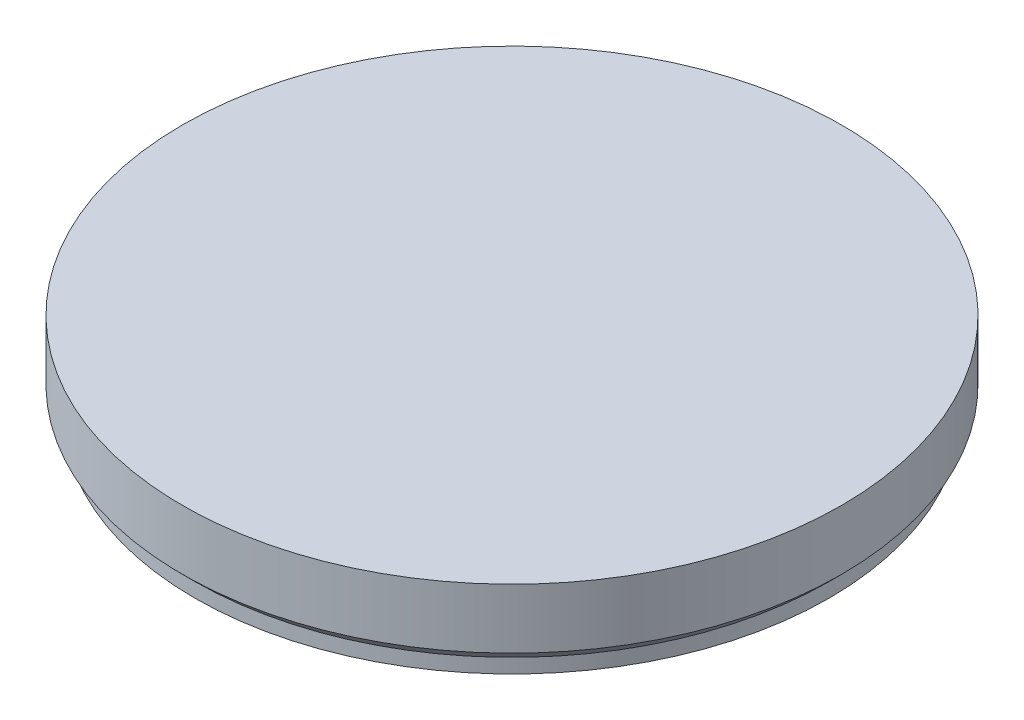
SolidWorks part; units mm, degrees
ref_plane "Front Plane" through (0, 0, 0) normal (0, 0, 1) x (1, 0, 0)
ref_plane "Top Plane" through (0, 0, 0) normal (0, 1, 0) x (1, 0, 0)
ref_plane "Right Plane" through (0, 0, 0) normal (1, 0, 0) x (0, 0, -1)
sketch "Sketch1" plane through (0, 0, 0) normal (0, 0, 1) x (1, 0, 0)
  line L0 (0, 12) -> (0, 15)
  line L1 (0, 15) -> (85, 15)
  line L2 (85, 15) -> (85, 10.5)
  line L3 (85, 10.5) -> (84, 10.5)
  line L4 (77, 3.5) -> (77, 0)
  line L5 (77, 0) -> (71, 0)
  line L6 (71, 0) -> (71, 12)
  line L7 (71, 12) -> (23.75, 12)
  line L8 (84, 10.5) -> (77, 3.5)
  line L9 (0, 12) -> (0, 9)
  line L10 (0, 9) -> (6.5, 9)
  line L11 (6.5, 9) -> (6.5, 6)
  line L12 (6.5, 6) -> (21.25, 6)
  line L13 (21.25, 6) -> (21.25, -7.5)
  line L15 (23.75, -7.5) -> (23.75, 12)
  line L16 (21.25, -7.5) -> (23.75, -7.5)
  point P6 (77, 10.5)
  dimension "D1" = 85
  dimension "D2" = 3
  dimension "D3" = 6
  dimension "D4" = 8
  dimension "D5" = 10.5
  dimension "D6" = 1.5
  dimension "D7" = 21.25
  dimension "D8" = 4.5
  dimension "D10" = 3
  dimension "D11" = 2.5
  dimension "D12" = 13.5
  dimension "D13" = 6.5
  dimension "D14" = 3
  dimension "D15" = 18
  dimension "D16" = 16.5
revolve "Revolve1" add sketch "Sketch1" angle 360 about L9
sketch "Sketch2" plane through (0, 12, 0) normal (0, -1, 0) x (1, 0, 0)
  line L1 (0, 70.2924) -> (-60.875, 35.1462)
  line L2 (-60.875, 35.1462) -> (-60.875, -35.1462)
  line L3 (-60.875, -35.1462) -> (0, -70.2924)
  line L4 (0, -70.2924) -> (60.875, -35.1462)
  line L5 (60.875, -35.1462) -> (60.875, 35.1462)
  line L6 (60.875, 35.1462) -> (0, 70.2924)
  circle A0 centre (0, 0) radius 71 construction
  circle A1 centre (0, 0) radius 71
  circle A2 centre (0, 0) radius 60.875 construction
  circle M8 centre (0, 0) radius 71
  dimension "D1" = 121.75
extrude "Boss-Extrude1" add sketch "Sketch2" along normal blind 11 contours L2 M8 | L1 M8 | L3 M8 | L4 M8 | L5 M8 | L6 M8
sketch "Sketch10" plane through (0, 15, 0) normal (0, 1, 0) x (1, 0, 0)
  line L0 (0, 99.1575) -> (0, -95.7853) construction
  line L1 (-99.194, 0) -> (98.9918, 0) construction
  line L2 (-55, 32) -> (-55, 9) construction
  line L3 (5, 9) -> (43.65, 9) construction
  line L4 (5, 9) -> (5, 32) construction
  line L5 (5, 32) -> (43.65, 32) construction
  line L6 (43.65, 9) -> (43.65, 32) construction
  line L7 (-50, 32) -> (-11.35, 32) construction
  line L8 (-50, 32) -> (-50, 9) construction
  line L9 (-50, 9) -> (-11.35, 9) construction
  line L10 (-11.35, 32) -> (-11.35, 9) construction
  line L11 (-50, 32) -> (-60, 32)
  line L12 (-50, 32) -> (-50, 9)
  line L13 (-50, 9) -> (-60, 9)
  line L14 (-60, 32) -> (-60, 9)
  line L15 (-50, 32) -> (-11.35, 32)
  line L16 (-50, 32) -> (-50, 40)
  line L17 (-50, 40) -> (-11.35, 40)
  line L18 (-11.35, 32) -> (-11.35, 40)
  line L19 (-50, 36) -> (-11.35, 36) construction
  line L20 (5, 32) -> (5, 40)
  line L21 (5, 36) -> (43.65, 36) construction
  line L22 (43.65, 32) -> (43.65, 40)
  line L23 (5, 32) -> (43.65, 32)
  line L24 (5, 40) -> (43.65, 40)
  line L25 (5, 32) -> (43.65, 32) construction
  line L26 (48.65, 32) -> (48.65, 9) construction
  line L27 (53.65, 32) -> (53.65, 9) construction
  line L28 (53.65, 32) -> (53.65, 9)
  line L29 (53.65, 32) -> (43.65, 32)
  line L30 (53.65, 9) -> (43.65, 9)
  line L31 (43.65, 32) -> (43.65, 9)
  line L32 (-49, 40) -> (-49, 32)
  line L33 (42.65, 40) -> (42.65, 32)
  circle A0 centre (-55, 26.5) radius 1.5
  circle A1 centre (-55, 14.5) radius 1.5
  circle A2 centre (-41, 36) radius 1.5
  circle A3 centre (-19.35, 36) radius 1.5
  circle A4 centre (13, 36) radius 1.5
  circle A5 centre (34.65, 36) radius 1.5
  circle A6 centre (48.65, 14.5) radius 1.5
  circle A7 centre (48.65, 26.5) radius 1.5
  circle A8 centre (0, 0) radius 81
  circle A9 centre (0, 0) radius 85
  circle M32 centre (0, 0) radius 85
  dimension "D11" = 3
  dimension "D12" = 5.5
  dimension "D14" = 3
  dimension "D19" = 3
  dimension "D22" = 3
  dimension "D1" = 23
  dimension "D2" = 38.65
  dimension "D3" = 40
  dimension "D4" = 5
  dimension "D5" = 16.35
  dimension "D6" = 23
  dimension "D7" = 38.65
  dimension "D9" = 10
  dimension "D10" = 8
  dimension "D13" = 5.5
  dimension "D15" = 8
  dimension "D16" = 8
  dimension "D17" = 8
  dimension "D18" = 8
  dimension "D20" = 10
  dimension "D21" = 5.5
  dimension "D23" = 5.5
  dimension "D24" = 1
  dimension "D25" = 1
sketch "Sketch12" plane through (0, 12, 0) normal (0, -1, 0) x (1, 0, 0)
  circle A0 centre (0, 0) radius 57.5
  circle A1 centre (0, 0) radius 23.75 construction
  circle A2 centre (0, 0) radius 23.75
  dimension "D1" = 115
extrude "Cut-Extrude8" cut sketch "Sketch12" against normal blind 1
extrude "Cut-Extrude9" cut sketch "Sketch10" against normal blind 10 contours A8 M32
sketch "Sketch14" plane through (0, 13, 0) normal (0, -1, 0) x (-1, 0, 0)
  circle A0 centre (0, 0) radius 23.75
  circle A1 centre (0, 0) radius 57.5
extrude "Boss-Extrude2" add sketch "Sketch14" against normal blind 1
sketch "Sketch15" plane through (0, 15, 0) normal (0, 1, 0) x (1, 0, 0)
  circle A1 centre (0, 0) radius 81
extrude "Boss-Extrude3" add sketch "Sketch15" along normal blind 4
sketch "Sketch16" plane through (0, 13, 0) normal (0, -1, 0) x (1, 0, 0)
  circle A0 centre (0, 0) radius 23.75
  circle A1 centre (0, 0) radius 57.5
extrude "Cut-Extrude11" cut sketch "Sketch16" against normal blind 2
sketch "Sketch17" plane through (0, 19, 0) normal (0, 1, 0) x (1, 0, 0)
  line L0 (-81, 0) -> (81, 0) construction
  line L1 (81, 0) -> (93.3398, 0) construction
  line L3 (-30.2086, 56.7255) -> (29.7914, 56.7255) construction
  line L4 (-30.2086, 56.7255) -> (-30.2086, -43.2745) construction
  line L5 (-30.2086, -43.2745) -> (29.7914, -43.2745) construction
  line L6 (29.7914, 56.7255) -> (29.7914, -43.2745) construction
  line L7 (-34.3336, 0) -> (-63.3336, 0)
  line L8 (33.9164, -10.11) -> (33.9164, 0)
  line L9 (33.9164, 0) -> (62.9164, 0)
  line L10 (62.9164, 0) -> (62.9164, -10.11)
  line L11 (62.9164, -10.11) -> (33.9164, -10.11)
  line L12 (-34.3336, 0) -> (-34.3336, -10.11)
  line L13 (-34.3336, -10.11) -> (-63.3336, -10.11)
  line L14 (-63.3336, -10.11) -> (-63.3336, 0)
  line L15 (-63.3336, 0) -> (-34.3336, 0)
  line L16 (-63.3336, 0) -> (-63.3336, 35.11)
  line L17 (-63.3336, 35.11) -> (-34.3336, 35.11)
  line L18 (-34.3336, 0) -> (-34.3336, 35.11)
  line L19 (33.9164, 0) -> (62.9164, 0)
  line L20 (33.9164, 0) -> (33.9164, 35.11)
  line L21 (33.9164, 35.11) -> (62.9164, 35.11)
  line L22 (62.9164, 0) -> (62.9164, 35.11)
  circle A0 centre (0, 0) radius 81 construction
  point P5 (0, 0)
  point P15 (33.9164, -5.055)
  dimension "D1" = 4.125
  dimension "D2" = 60
  dimension "D3" = 4.125
extrude "Boss-Extrude4" add sketch "Sketch17" along normal blind 3 contours L14 L13 L12 L7 | L7 L18 L17 L16 | L11 L10 L9 L8 | L9 L22 L21 L20
sketch "Sketch19" plane through (0, 19, 0) normal (0, 1, 0) x (1, 0, 0)
  circle A0 centre (0, 0) radius 80.9709
extrude "Boss-Extrude5" add sketch "Sketch19" along normal blind 2
sketch "Sketch20" plane through (0, 21, 0) normal (0, 1, 0) x (1, 0, 0)
  circle A0 centre (0, 0) radius 80.9709
extrude "Boss-Extrude6" add sketch "Sketch20" against normal blind 3
sketch "Sketch21" plane through (0, 22, 0) normal (0, 1, 0) x (1, 0, 0)
  line L0 (33.9164, 35.11) -> (62.9164, 35.11) construction
  line L1 (33.9164, 35.11) -> (62.9164, 35.11)
  line L2 (33.9164, 35.11) -> (33.9164, -10.11)
  line L3 (33.9164, -10.11) -> (62.9164, -10.11)
  line L4 (62.9164, 35.11) -> (62.9164, -10.11)
  line L5 (-63.3336, 35.11) -> (-34.3336, 35.11)
  line L6 (-63.3336, 35.11) -> (-63.3336, -10.11)
  line L7 (-63.3336, -10.11) -> (-34.3336, -10.11)
  line L8 (-34.3336, 35.11) -> (-34.3336, -10.11)
  line L9 (33.9164, 35.11) -> (62.9164, 35.11) construction
extrude "Boss-Extrude7" add sketch "Sketch21" along normal blind 4
sketch "Sketch22" plane through (0, 21, 0) normal (0, 1, 0) x (1, 0, 0)
  line L0 (48.4164, 35.11) -> (37.4164, 35.11)
  line L18 (33.9164, 35.11) -> (62.9164, 35.11) construction
  line L22 (37.4164, 35.11) -> (37.4164, 50.11)
  line L24 (48.4164, 35.11) -> (59.4164, 35.11)
  line L25 (59.4164, 35.11) -> (59.4164, 50.11)
  line L26 (59.4164, 50.11) -> (37.4164, 50.11)
  point P0 (48.4164, 35.11)
extrude "Boss-Extrude9" add sketch "Sketch22" along normal up to surface (5 mm away) up to face at (48.4164, 26, -12.5)
sketch "Sketch26" plane through (0, 26, 0) normal (0, 1, 0) x (1, 0, 0)
  circle A0 centre (0, 0) radius 80.9709
extrude "Cut-Extrude12" cut sketch "Sketch26" against normal up to surface (5 mm away) up to face at (-48.8336, 21, -12.5)
sketch "Sketch27" plane through (0, 21, 0) normal (0, 1, 0) x (1, 0, 0)
  circle A0 centre (0, 0) radius 80.9709
extrude "Boss-Extrude10" add sketch "Sketch27" against normal blind 4
sketch "Sketch28" plane through (0, 21, 0) normal (0, 1, 0) x (1, 0, 0)
  circle A0 centre (0, 0) radius 80.9709
  circle A1 centre (0, 0) radius 80
extrude "Cut-Extrude15" cut sketch "Sketch28" against normal up to next
sketch "Sketch29" plane through (0, 21, 0) normal (0, 1, 0) x (1, 0, 0)
  line L0 (-80, 0) -> (80, 0) construction
  line L1 (-31.9948, 40.3777) -> (31.9948, 40.3777)
  line L2 (-31.9948, 40.3777) -> (-31.9948, -40.3777)
  line L3 (-31.9948, -40.3777) -> (31.9948, -40.3777)
  line L4 (31.9948, 40.3777) -> (31.9948, -40.3777)
  line L5 (-31.9948, 40.3777) -> (31.9948, -40.3777) construction
  line L6 (-31.9948, -40.3777) -> (31.9948, 40.3777) construction
  line L7 (31.9948, 40.3777) -> (69.2448, 40.3777)
  line L8 (31.9948, 40.3777) -> (31.9948, -30.8491)
  line L9 (31.9948, -30.8491) -> (69.2448, -30.8491)
  line L10 (69.2448, 40.3777) -> (69.2448, -30.8491)
  line L11 (-31.9948, 40.3777) -> (-69.2448, 40.3777)
  line L12 (-31.9948, 40.3777) -> (-31.9948, -36.8045)
  line L13 (-31.9948, -36.8045) -> (-69.2448, -36.8045)
  line L14 (-69.2448, 40.3777) -> (-69.2448, -36.8045)
  line L15 (-50.6198, -36.8045) -> (-50.6198, 69.5608) construction
  line L16 (50.6198, -30.8491) -> (50.6198, 69.5608) construction
  line L17 (-77.4849, 35.11) -> (91.1224, 35.11) construction
  line L18 (34.4948, 18.2921) -> (66.7448, 18.2921)
  line L19 (34.4948, 18.2921) -> (34.4948, -18.2921)
  line L20 (34.4948, -18.2921) -> (66.7448, -18.2921)
  line L21 (66.7448, 18.2921) -> (66.7448, -18.2921)
  line L22 (34.4948, 18.2921) -> (66.7448, -18.2921) construction
  line L23 (34.4948, -18.2921) -> (66.7448, 18.2921) construction
  line L24 (-66.7448, 18.41) -> (-34.4948, 18.41)
  line L25 (-66.7448, 18.41) -> (-66.7448, -18.41)
  line L26 (-66.7448, -18.41) -> (-34.4948, -18.41)
  line L27 (-34.4948, 18.41) -> (-34.4948, -18.41)
  line L28 (-66.7448, 18.41) -> (-34.4948, -18.41) construction
  line L29 (-66.7448, -18.41) -> (-34.4948, 18.41) construction
  line L30 (-66.7448, 18.41) -> (-34.4948, 18.41)
  line L31 (-66.7448, 18.41) -> (-66.7448, 26.81)
  line L32 (-66.7448, 26.81) -> (-34.4948, 26.81)
  line L33 (-34.4948, 18.41) -> (-34.4948, 26.81)
  line L34 (34.4948, 18.2921) -> (66.7448, 18.2921)
  line L35 (34.4948, 18.2921) -> (34.4948, 26.6921)
  line L36 (34.4948, 26.6921) -> (66.7448, 26.6921)
  line L37 (66.7448, 18.2921) -> (66.7448, 26.6921)
  line L38 (-66.7448, 26.81) -> (-34.4948, 26.81)
  line L39 (-66.7448, 26.81) -> (-66.7448, 35.11)
  line L40 (-66.7448, 35.11) -> (-34.4948, 35.11)
  line L41 (-34.4948, 26.81) -> (-34.4948, 35.11)
  line L42 (34.4948, 26.6921) -> (66.7448, 26.6921)
  line L43 (34.4948, 26.6921) -> (34.4948, 34.9921)
  line L44 (34.4948, 34.9921) -> (66.7448, 34.9921)
  line L45 (66.7448, 26.6921) -> (66.7448, 34.9921)
  line L46 (-153.0815, -10.41) -> (80, -10.41) construction
  circle A0 centre (0, 0) radius 80 construction
  point P0 (0, 0)
  point P21 (-50.6198, 0)
  point P23 (50.6198, 0)
  dimension "D2" = 2.5
  dimension "D1" = 18.625
  dimension "D3" = 2.5
  dimension "D4" = 2.5
  dimension "D5" = 13.6856
  dimension "D6" = 10.41
  dimension "D7" = 10.7552
